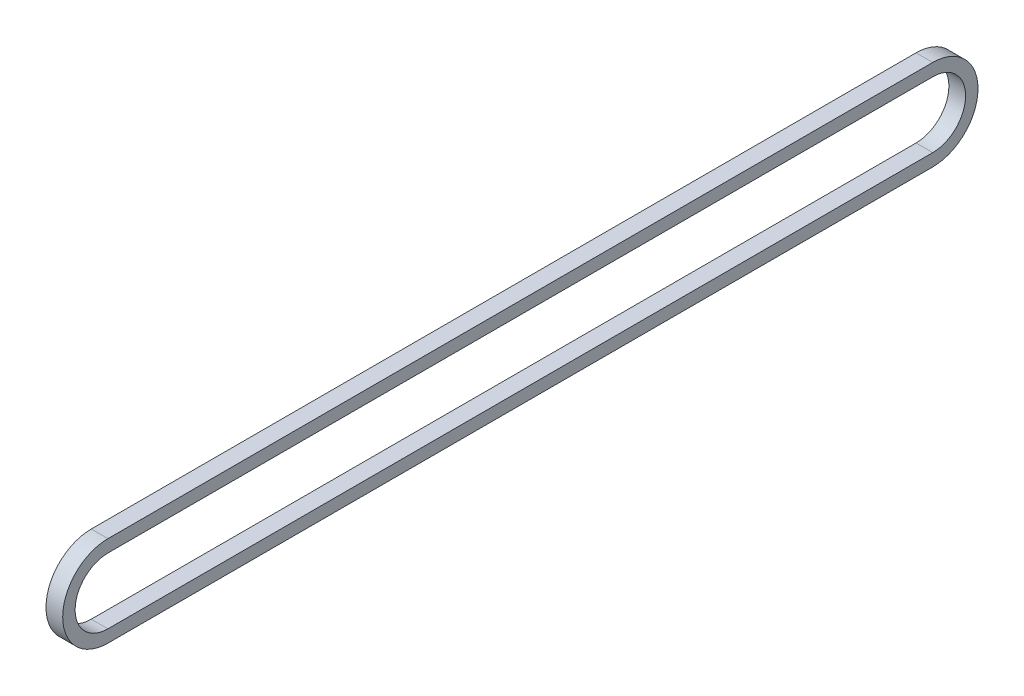
SolidWorks part; units mm, degrees
material "6061-T6 (SS)"
ref_plane "Front Plane" through (0, 0, 0) normal (0, 0, 1) x (1, 0, 0)
ref_plane "Top Plane" through (0, 0, 0) normal (0, 1, 0) x (1, 0, 0)
ref_plane "Right Plane" through (0, 0, 0) normal (1, 0, 0) x (0, 0, -1)
sketch "Sketch1" plane through (0, 0, 0) normal (1, 0, 0) x (0, 0, -1)
  line L0 (0, 18.1864) -> (384.1726, 18.1864)
  line L1 (0, -18.1864) -> (384.1726, -18.1864)
  line L2 (0, 21.082) -> (384.1726, 21.082)
  line L3 (0, -21.082) -> (384.1726, -21.082)
  line L4 (0, 15.2908) -> (384.1726, 15.2908)
  line L5 (0, -15.2908) -> (384.1726, -15.2908)
  arc A0 (0, 18.1864) -> (0, -18.1864) centre (0, 0) ccw
  arc A1 (384.1726, -18.1864) -> (384.1726, 18.1864) centre (384.1726, 0) ccw
  arc A2 (384.1726, -21.082) -> (384.1726, 21.082) centre (384.1726, 0) ccw
  arc A3 (0, 21.082) -> (0, -21.082) centre (0, 0) ccw
  arc A4 (384.1726, -15.2908) -> (384.1726, 15.2908) centre (384.1726, 0) ccw
  arc A5 (0, 15.2908) -> (0, -15.2908) centre (0, 0) ccw
  dimension "D1" = 36.3728
  dimension "D2" = 882.6137
  dimension "D5" = 384.1726
  dimension "D3" = 2.8956
  dimension "D4" = 2.8956
extrude "Boss-Extrude1" add sketch "Sketch1" along normal mid plane 7.7724 contours L2 A2 L3 A3 | L4 A4 L5 A5
